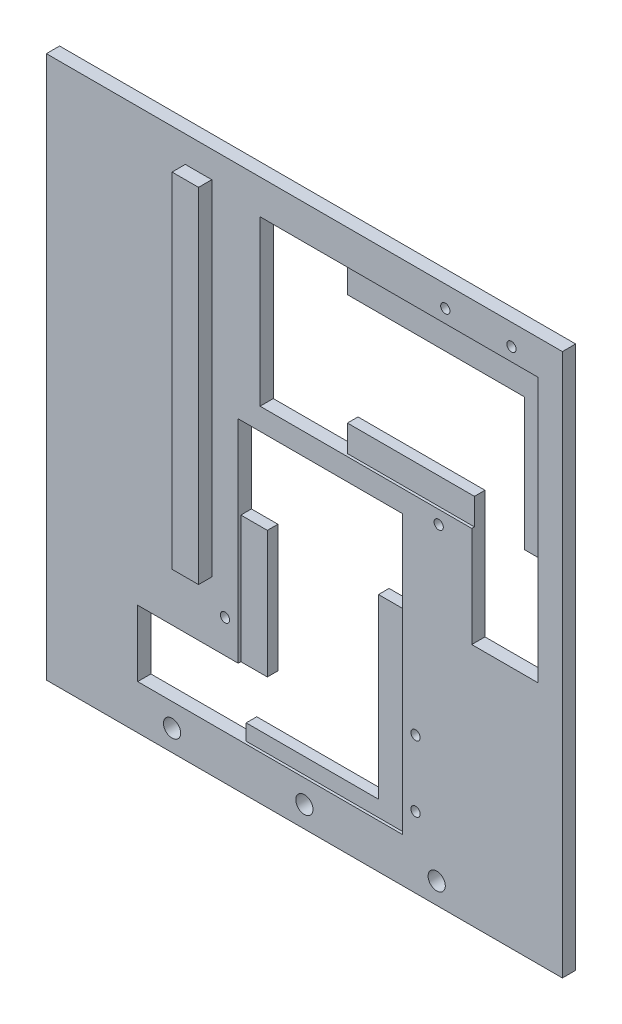
SolidWorks part; units mm, degrees
ref_plane "Front Plane" through (0, 0, 0) normal (0, 0, 1) x (1, 0, 0)
ref_plane "Top Plane" through (0, 0, 0) normal (0, 1, 0) x (1, 0, 0)
ref_plane "Right Plane" through (0, 0, 0) normal (1, 0, 0) x (0, 0, -1)
sketch "Sketch1" plane through (0, 0, 0) normal (0, 0, 1) x (1, 0, 0)
  line L1 (-97.5, 0) -> (97.5, 0)
  line L24 (-97.5, 0) -> (-97.5, -205)
  line L27 (-97.5, -205) -> (97.5, -205)
  line L30 (97.5, -205) -> (97.5, 0)
  point P34 (0, 0)
  dimension "D6" = 205
  dimension "D7" = 195
extrude "Boss-Extrude1" add sketch "Sketch1" along normal blind 5
sketch "Sketch5" plane through (0, 0, 5) normal (0, 0, 1) x (1, 0, 0)
  line L0 (-25, -83.25) -> (37, -83.25)
  line L1 (37, -83.25) -> (37, -188.25)
  line L2 (37, -188.25) -> (-63, -188.25)
  line L3 (-63, -188.25) -> (-63, -163.25)
  line L4 (-63, -163.25) -> (-25, -163.25)
  line L5 (-25, -163.25) -> (-25, -83.25)
  line L6 (0, -100) -> (0, -188.25) construction
  line L7 (97.5, 0) -> (-97.5, 0) construction
  line L10 (-25, -100) -> (0, -100) construction
  line L13 (88.25, -113) -> (63.25, -113)
  line L14 (88.25, -13) -> (88.25, -113)
  line L15 (0, -14.25) -> (0, -13) construction
  line L16 (0, -14.25) -> (0, -48.75) construction
  line L17 (0, -73.75) -> (0, -75) construction
  line L18 (-16.75, -13) -> (88.25, -13)
  line L19 (63.25, -113) -> (63.25, -75)
  line L20 (63.25, -75) -> (-16.75, -75)
  line L21 (0, -48.75) -> (88.25, -48.75) construction
  line L22 (-16.75, -75) -> (-16.75, -13)
  line L23 (0, -100) -> (34.5, -100) construction
  line L24 (0, -48.75) -> (0, -73.75) construction
  dimension "D1" = 105
  dimension "D2" = 62
  dimension "D3" = 59.5
  dimension "D4" = 13
  dimension "D5" = 100
  dimension "D6" = 25
  dimension "D7" = 25
  dimension "D8" = 88.25
  dimension "D9" = 8.25
extrude "Cut-Extrude2" cut sketch "Sketch5" against normal through all
sketch "Sketch6" plane through (0, 0, 0) normal (0, 0, -1) x (-1, 0, 0)
  line L0 (25, -115.25) -> (25, -163.25)
  line L1 (25, -83.25) -> (25, -163.25) construction
  line L2 (25, -163.25) -> (15, -163.25)
  line L3 (15, -163.25) -> (15, -115.25)
  line L4 (15, -115.25) -> (25, -115.25)
  line L5 (23, -188.25) -> (23, -182.25)
  line L6 (63, -188.25) -> (-37, -188.25) construction
  line L7 (23, -182.25) -> (-27, -182.25)
  line L8 (-27, -182.25) -> (-27, -115.25)
  line L9 (-27, -115.25) -> (-37, -115.25)
  line L10 (-37, -188.25) -> (-37, -83.25) construction
  line L11 (23, -188.25) -> (-37, -188.25)
  line L12 (-37, -188.25) -> (-37, -115.25)
  line L13 (63, -188.25) -> (-37, -188.25) construction
  line L14 (25, -163.25) -> (63, -163.25) construction
  line L15 (-88.25, -73) -> (-82.25, -73)
  line L16 (-63.25, -75) -> (-15.25, -75)
  line L17 (-63.25, -75) -> (-63.25, -65)
  line L18 (-63.25, -65) -> (-15.25, -65)
  line L19 (-15.25, -75) -> (-15.25, -65)
  line L20 (-88.25, -113) -> (-88.25, -13) construction
  line L21 (-82.25, -73) -> (-82.25, -23)
  line L22 (-82.25, -23) -> (-15.25, -23)
  line L23 (-15.25, -23) -> (-15.25, -13)
  line L24 (-88.25, -13) -> (16.75, -13) construction
  line L25 (-15.25, -13) -> (-88.25, -13)
  line L26 (-88.25, -13) -> (-88.25, -73)
  dimension "D1" = 73
  dimension "D2" = 73
  dimension "D4" = 6
  dimension "D5" = 10
  dimension "D6" = 10
  dimension "D7" = 60
extrude "Boss-Extrude3" add sketch "Sketch6" against normal blind 4
sketch "Sketch11" plane through (0, 0, 5) normal (0, 0, 1) x (1, 0, 0)
  line L1 (-30, -150.75) -> (-30, -163.25) construction
  line L2 (-25, -163.25) -> (-63, -163.25) construction
  line L3 (-30, -150.75) -> (-25, -150.75) construction
  line L4 (-25, -83.25) -> (-25, -163.25) construction
  line L6 (50.75, -80) -> (50.75, -75) construction
  line L7 (-16.75, -75) -> (63.25, -75) construction
  line L8 (50.75, -80) -> (63.25, -80) construction
  line L9 (63.25, -75) -> (63.25, -113) construction
  line L10 (42, -153.25) -> (42, -178.25) construction
  line L11 (37, -188.25) -> (37, -83.25) construction
  line L13 (53.25, -8) -> (78.25, -8) construction
  line L14 (42, -153.25) -> (42, -143.25) construction
  line L16 (88.25, -13) -> (88.25, -8) construction
  line L17 (88.25, -8) -> (78.25, -8) construction
  line L18 (37, -188.25) -> (42, -188.25) construction
  line L19 (42, -188.25) -> (42, -178.25) construction
  line L20 (-63, -188.25) -> (37, -188.25) construction
  circle A0 centre (42, -153.25) radius 1.75
  circle A1 centre (42, -178.25) radius 1.75
  circle A3 centre (-30, -150.75) radius 1.75
  circle A5 centre (50.75, -80) radius 1.75
  circle A6 centre (53.25, -8) radius 1.75
  circle A7 centre (78.25, -8) radius 1.75
  dimension "D1" = 3.5
  dimension "D2" = 25
  dimension "D3" = 5
  dimension "D4" = 5
  dimension "D6" = 45
  dimension "D7" = 37.5
extrude "Retainer Holes" cut sketch "Sketch11" against normal through all
sketch "Sketch14" plane through (0, 0, 5) normal (0, 0, 1) x (1, 0, 0)
  line L0 (-50, -197) -> (50, -197) construction
  line L1 (0, -197) -> (0, -205) construction
  line L2 (-97.5, -205) -> (97.5, -205) construction
  circle A0 centre (-50, -197) radius 3.25
  circle A1 centre (50, -197) radius 3.25
  circle A2 centre (0, -197) radius 3.25
  dimension "D1" = 6.5
  dimension "D2" = 8
  dimension "D3" = 100
extrude "Handle Mount" cut sketch "Sketch14" against normal through all
sketch "Sketch12" plane through (0, 0, 5) normal (0, 0, 1) x (1, 0, 0)
  line L0 (-25, -83.25) -> (-25, -163.25) construction
  line L1 (-45, -10) -> (-35, -10)
  line L2 (-45, -10) -> (-45, -140)
  line L3 (-45, -140) -> (-35, -140)
  line L4 (-35, -10) -> (-35, -140)
  line L5 (97.5, 0) -> (-97.5, 0) construction
  dimension "D1" = 10
  dimension "D2" = 130
  dimension "D3" = 10
  dimension "D4" = 10
extrude "Ribs" add sketch "Sketch12" along normal blind 5
